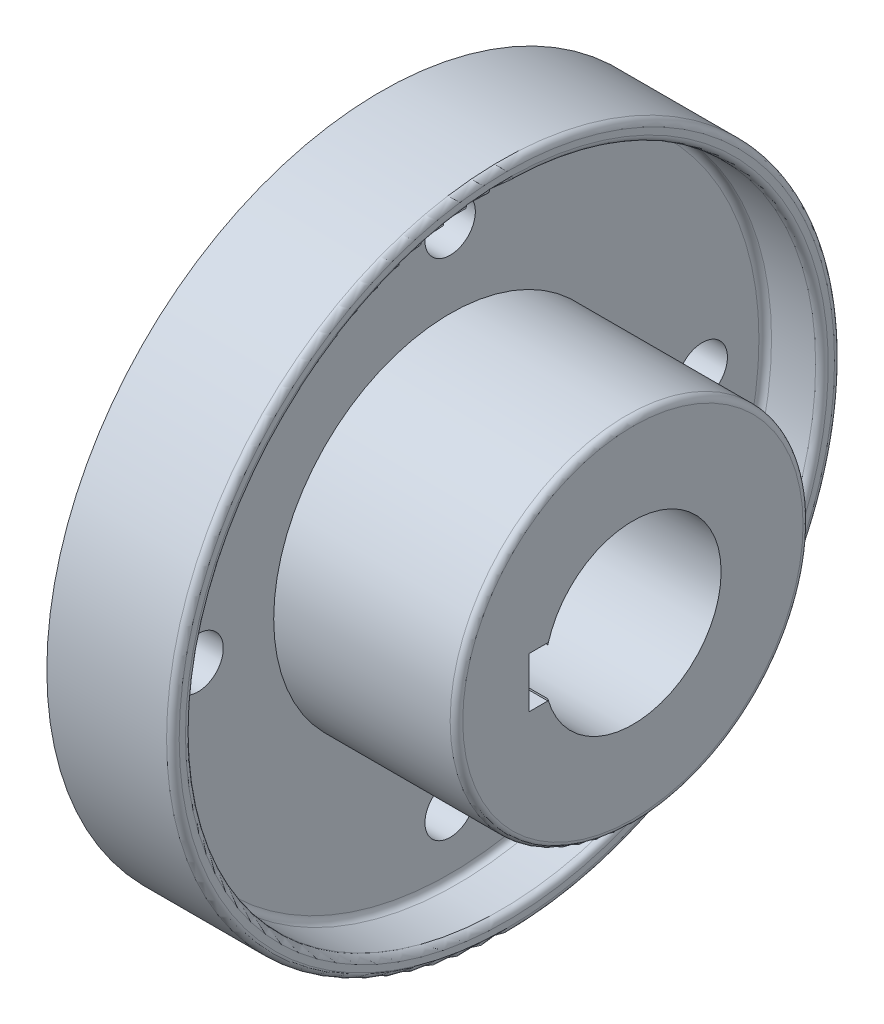
SolidWorks part; units mm, degrees
ref_plane "Front Plane" through (0, 0, 0) normal (0, 0, 1) x (1, 0, 0)
ref_plane "Top Plane" through (0, 0, 0) normal (0, 1, 0) x (1, 0, 0)
ref_plane "Right Plane" through (0, 0, 0) normal (1, 0, 0) x (0, 0, -1)
sketch "Sketch1" plane through (0, 0, 0) normal (0, 0, 1) x (1, 0, 0)
  line L0 (0, 0) -> (80, 0)
  line L1 (80, 0) -> (80, 54)
  line L2 (78, 56) -> (28.2927, 56)
  line L3 (40, 104) -> (40, 102)
  line L4 (38, 106) -> (0, 106)
  line L5 (0, 106) -> (0, 0)
  line L6 (38, 100) -> (24, 100)
  line L7 (22, 98) -> (22, 56)
  line L8 (22, 56) -> (28.2927, 56)
  arc A0 (24, 100) -> (22, 98) centre (24, 98) ccw
  arc A1 (40, 102) -> (38, 100) centre (38, 102) cw
  arc A2 (40, 104) -> (38, 106) centre (38, 104) ccw
  arc A3 (80, 54) -> (78, 56) centre (78, 54) ccw
  point P16 (40, 106)
  point P19 (80, 56)
  dimension "D7" = 2
  dimension "D8" = 2
  dimension "D1" = 80
  dimension "D2" = 56
  dimension "D3" = 106
  dimension "D4" = 22
  dimension "D5" = 40
  dimension "D6" = 6
revolve "Revolve1" add sketch "Sketch1" angle 360 about L0
sketch "Sketch2" plane through (80, 0, 0) normal (1, 0, 0) x (0, 0, -1)
  circle A0 centre (0, 0) radius 28
  dimension "D1" = 56
extrude "Cut-Extrude1" cut sketch "Sketch2" against normal through all
sketch "Sketch3" plane through (0, 0, 0) normal (-1, 0, 0) x (0, 0, 1)
  circle A0 centre (0, 0) radius 46
  dimension "D1" = 92
extrude "Cut-Extrude2" cut sketch "Sketch3" against normal blind 6
sketch "Sketch4" plane through (6, 0, 0) normal (-1, 0, 0) x (0, 0, 1)
  line L0 (0, 0) -> (116.0779, 0) construction
  line L2 (27, -8) -> (33, -8)
  line L3 (27, -8) -> (27, 8)
  line L4 (27, 8) -> (33, 8)
  line L5 (33, -8) -> (33, 8)
  line L6 (27, -8) -> (33, 8) construction
  line L7 (27, 8) -> (33, -8) construction
  point P3 (30, 0)
  dimension "D1" = 16
  dimension "D2" = 30
  dimension "D3" = 6
extrude "Cut-Extrude6" cut sketch "Sketch4" against normal through all
sketch "Sketch5" plane through (0, 0, 0) normal (-1, 0, 0) x (0, 0, 1)
  line L0 (0, 106) -> (0, -106) construction
  line L1 (106, 0) -> (-106, 0) construction
  circle A0 centre (0, 0) radius 106 construction
  circle A1 centre (0, 80) radius 8
  dimension "D2" = 16
  dimension "D1" = 80
extrude "Cut-Extrude7" cut sketch "Sketch5" against normal through all
pattern_circular "CirPattern1" count 4 over 360 about axis through (0, 0, 0) along (1, 0, 0) of "Cut-Extrude7"
